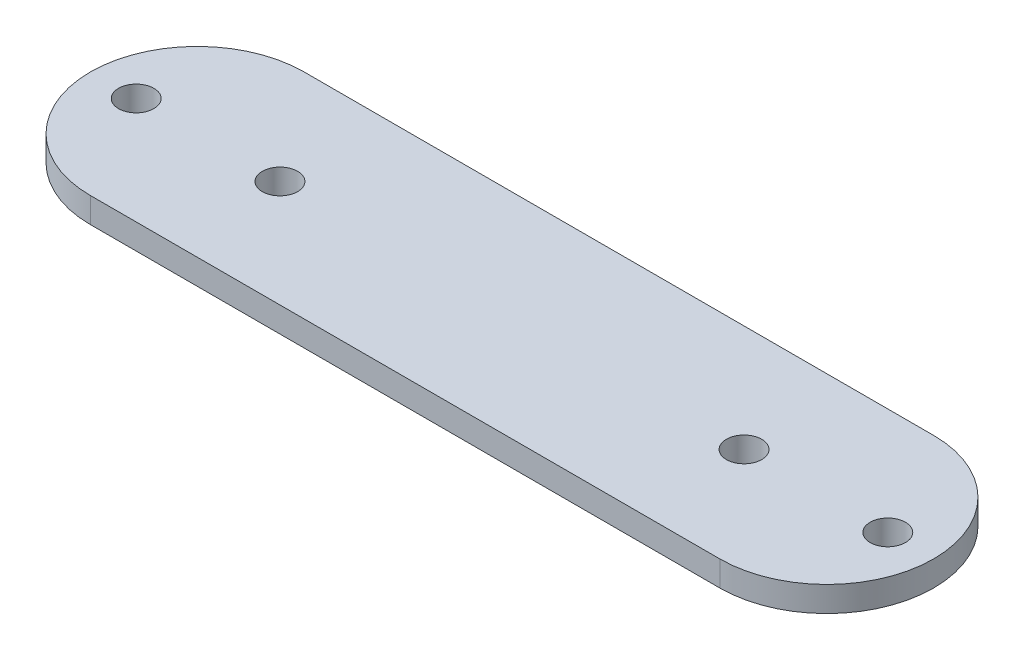
SolidWorks part; units mm, degrees
material "6061 Alloy"
ref_plane "Front Plane" through (0, 0, 0) normal (0, 0, 1) x (1, 0, 0)
ref_plane "Top Plane" through (0, 0, 0) normal (0, 1, 0) x (1, 0, 0)
ref_plane "Right Plane" through (0, 0, 0) normal (1, 0, 0) x (0, 0, -1)
sketch "Sketch1" plane through (0, 0, 0) normal (0, 1, 0) x (1, 0, 0)
  line L0 (-31.2, 0) -> (31.2, 0) construction
  line L1 (-31.2, 10.6) -> (31.2, 10.6)
  line L2 (-31.2, -10.6) -> (31.2, -10.6)
  arc A0 (-31.2, 10.6) -> (-31.2, -10.6) centre (-31.2, 0) ccw
  arc A1 (31.2, -10.6) -> (31.2, 10.6) centre (31.2, 0) ccw
  point P3 (0, 0)
  dimension "D1" = 21.2
  dimension "D2" = 62.4
extrude "Boss-Extrude1" add sketch "Sketch1" along normal blind 2.5
sketch "Sketch2" plane through (0, 2.5, 0) normal (0, 1, 0) x (1, 0, 0)
  circle A0 centre (-37.25, 0) radius 1.75
  circle A1 centre (-23, 0) radius 1.75
  circle A2 centre (23, 0) radius 1.75
  circle A3 centre (37.25, 0) radius 1.75
  dimension "D1" = 3.5
  dimension "D2" = 23
  dimension "D3" = 46
  dimension "D5" = 74.5
  dimension "D4" = 37.25
extrude "Cut-Extrude1" cut sketch "Sketch2" against normal through all
